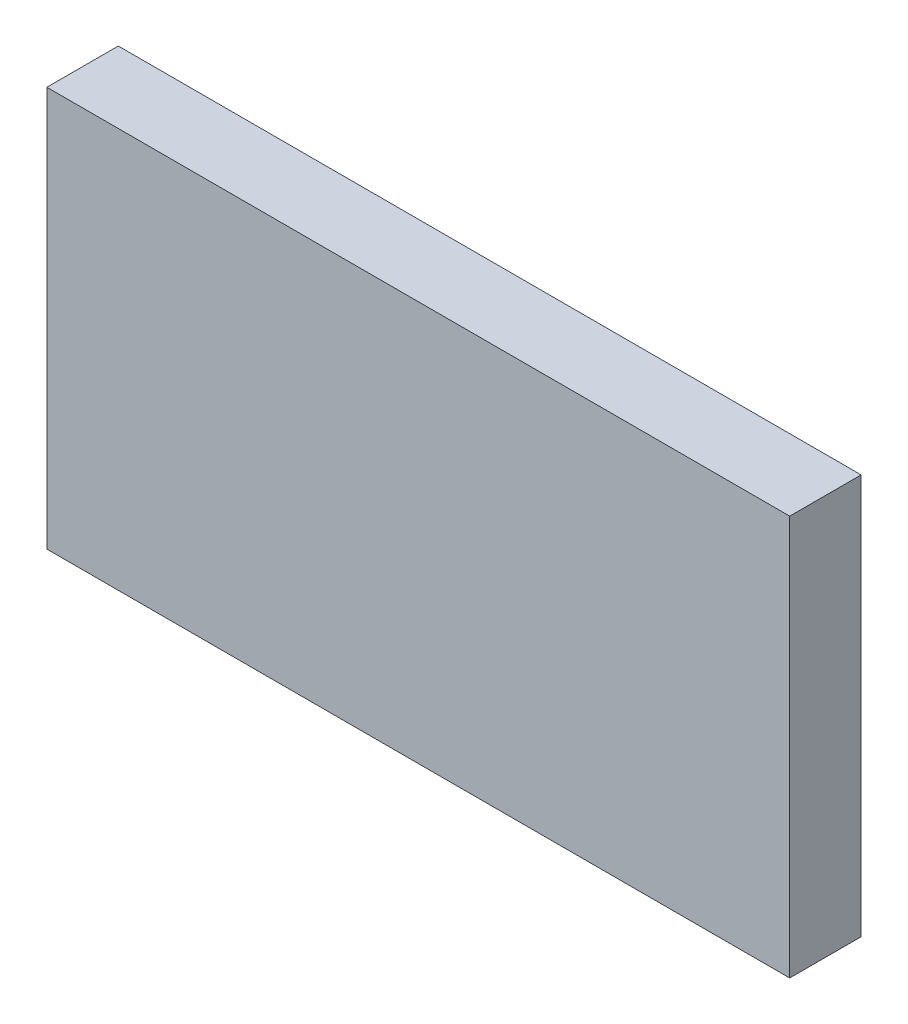
SolidWorks part; units mm, degrees
ref_plane "Front Plane" through (0, 0, 0) normal (0, 0, 1) x (1, 0, 0)
ref_plane "Top Plane" through (0, 0, 0) normal (0, 1, 0) x (1, 0, 0)
ref_plane "Right Plane" through (0, 0, 0) normal (1, 0, 0) x (0, 0, -1)
sketch "Sketch1" plane through (0, 0, 0) normal (0, 1, 0) x (1, 0, 0)
  line L1 (0, 0) -> (26, 0)
  line L2 (0, 0) -> (0, 2.5)
  line L3 (0, 2.5) -> (26, 2.5)
  line L4 (26, 0) -> (26, 2.5)
  dimension "D1" = 26
  dimension "D2" = 2.5
extrude "Boss-Extrude1" add sketch "Sketch1" along normal blind 14
